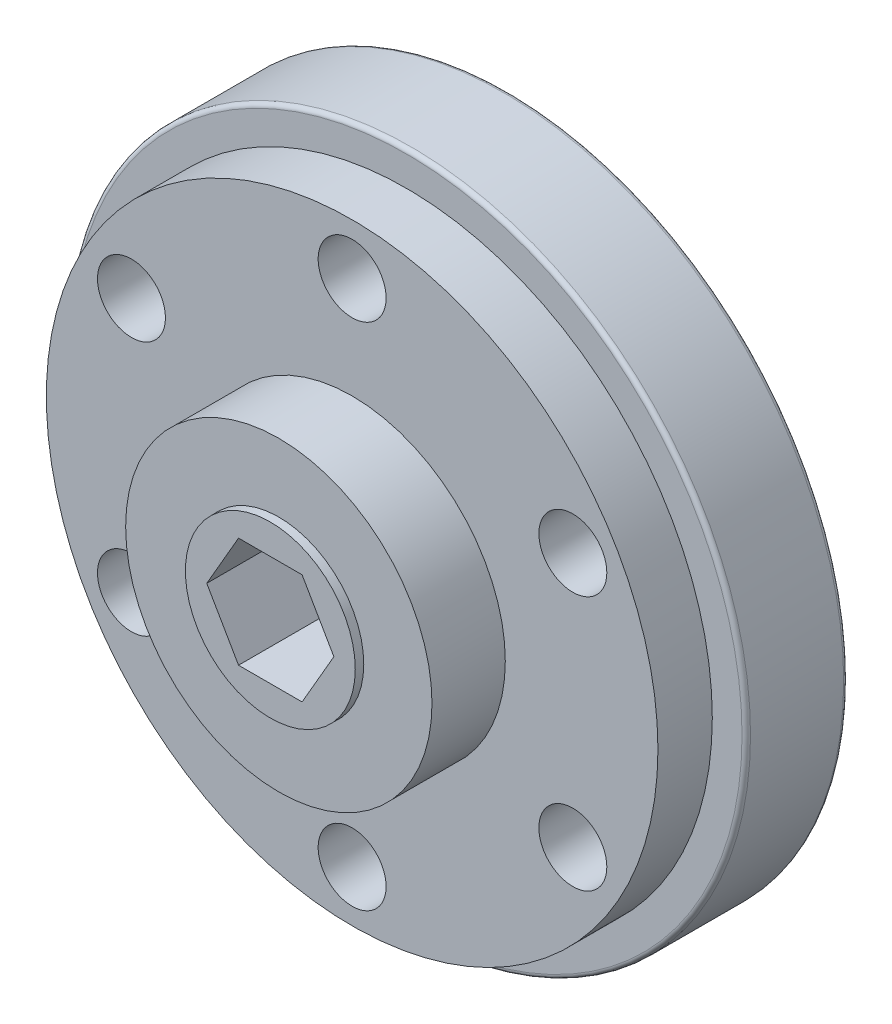
SolidWorks part; units mm, degrees
material "ABS"
ref_plane "Front" through (0, 0, 0) normal (0, 0, 1) x (1, 0, 0)
ref_plane "Top" through (0, 0, 0) normal (0, 1, 0) x (1, 0, 0)
ref_plane "Right" through (0, 0, 0) normal (1, 0, 0) x (0, 0, -1)
sketch "Sketch1" plane through (0, 0, 0) normal (0, 0, 1) x (1, 0, 0)
  line L1 (2.9696, -5.1435) -> (5.9392, 0)
  line L2 (5.9392, 0) -> (2.9696, 5.1435)
  line L3 (2.9696, 5.1435) -> (-2.9696, 5.1435)
  line L4 (-2.9696, 5.1435) -> (-5.9392, 0)
  line L5 (-5.9392, 0) -> (-2.9696, -5.1435)
  line L6 (-2.9696, -5.1435) -> (2.9696, -5.1435)
  circle A0 centre (0, 0) radius 31.75
  circle A1 centre (0, 0) radius 5.1435 construction
  dimension "D1" = 63.5
  dimension "D2" = 10.287
extrude "Boss-Extrude1" add sketch "Sketch1" along normal blind 22.225
sketch "Sketch2" plane through (0, 0, 0) normal (0, 0, -1) x (-1, 0, 0)
  circle A0 centre (0, 0) radius 7.9375
  circle A1 centre (0, 0) radius 13.4938
  dimension "D1" = 15.875
  dimension "D2" = 26.9875
extrude "Cut-Extrude1" cut sketch "Sketch2" against normal blind 1.5875
sketch "Sketch3" plane through (0, 0, 22.225) normal (0, 0, 1) x (1, 0, 0)
  circle A0 centre (0, 0) radius 14.3129
  dimension "D1" = 28.6258
extrude "Cut-Extrude2" cut sketch "Sketch3" against normal blind 7.6454 flip side to cut
sketch "Sketch7" plane through (0, 0, 14.5796) normal (0, 0, 1) x (1, 0, 0)
  circle A0 centre (0, 0) radius 28.575
  dimension "D1" = 57.15
extrude "Cut-Extrude3" cut sketch "Sketch7" against normal blind 5.08 flip side to cut
hole_wizard "#10 Clearance Hole1" positions "Sketch4" profile "Sketch5" hole size "#10" standard "ANSI Inch" end condition through all
sketch "Sketch4" plane through (0, 0, 14.5796) normal (0, 0, 1) x (1, 0, 0)
  line L0 (0, 0) -> (0, 31.75) construction
  circle A0 centre (0, 0) radius 31.75 construction
  point P9 (0, 23.8125)
  dimension "D1" = 23.8125
sketch "Sketch5" plane through (0, 23.8125, 14.5796) normal (1, 0, 0) x (0, -1, 0)
  line L0 (0, 0) -> (0, 14.5796)
  line L1 (0, 14.5796) -> (3.175, 14.5796)
  line L2 (3.175, 14.5796) -> (3.175, 0)
  line L5 (3.175, 0) -> (0, 0)
  line L11 (0, -6.35) -> (0, 107.95) construction
  dimension "Thru Hole Dia." = 6.35
  dimension "Thru Hole Depth" = 14.5796
sketch "Sketch8" plane through (0, 0, 0) normal (0, 0, -1) x (-1, 0, 0)
  line L1 (3.0063, 18.6055) -> (6.0125, 23.8125)
  line L2 (6.0125, 23.8125) -> (3.0063, 29.0195)
  line L3 (3.0063, 29.0195) -> (-3.0063, 29.0195)
  line L4 (-3.0063, 29.0195) -> (-6.0125, 23.8125)
  line L5 (-6.0125, 23.8125) -> (-3.0063, 18.6055)
  line L6 (-3.0063, 18.6055) -> (3.0063, 18.6055)
  circle A0 centre (0, 23.8125) radius 5.207 construction
  dimension "D1" = 10.414
extrude "Cut-Extrude4" cut sketch "Sketch8" against normal blind 6.35
pattern_circular "CirPattern1" count 6 over 360 about axis through (0, 0, 0) along (0, 0, 1) of "#10 Clearance Hole1", "Cut-Extrude4"
sketch "Sketch9" plane through (0, 0, 6.35) normal (0, 0, -1) x (-1, 0, 0)
  line L0 (-17.616, 6.6992) -> (-14.6097, 11.9062) construction
  circle A0 centre (0, 0) radius 18.6055
  circle A1 centre (0, 0) radius 29.1748
extrude "Boss-Extrude2" add sketch "Sketch9" against normal blind 0.6
fillet "Fillet1" radius 0.3969 4 edges at (31.75, 0, 0) (-7.9375, 0, 0) (-13.4937, 0, 0) (31.75, 0, 9.4996)
sketch "Sketch10" plane through (0, 0, 22.225) normal (0, 0, 1) x (1, 0, 0)
  circle A0 centre (0, 0) radius 7.9375
  dimension "D1" = 15.875
extrude "Cut-Extrude5" cut sketch "Sketch10" against normal blind 0.7937 flip side to cut
